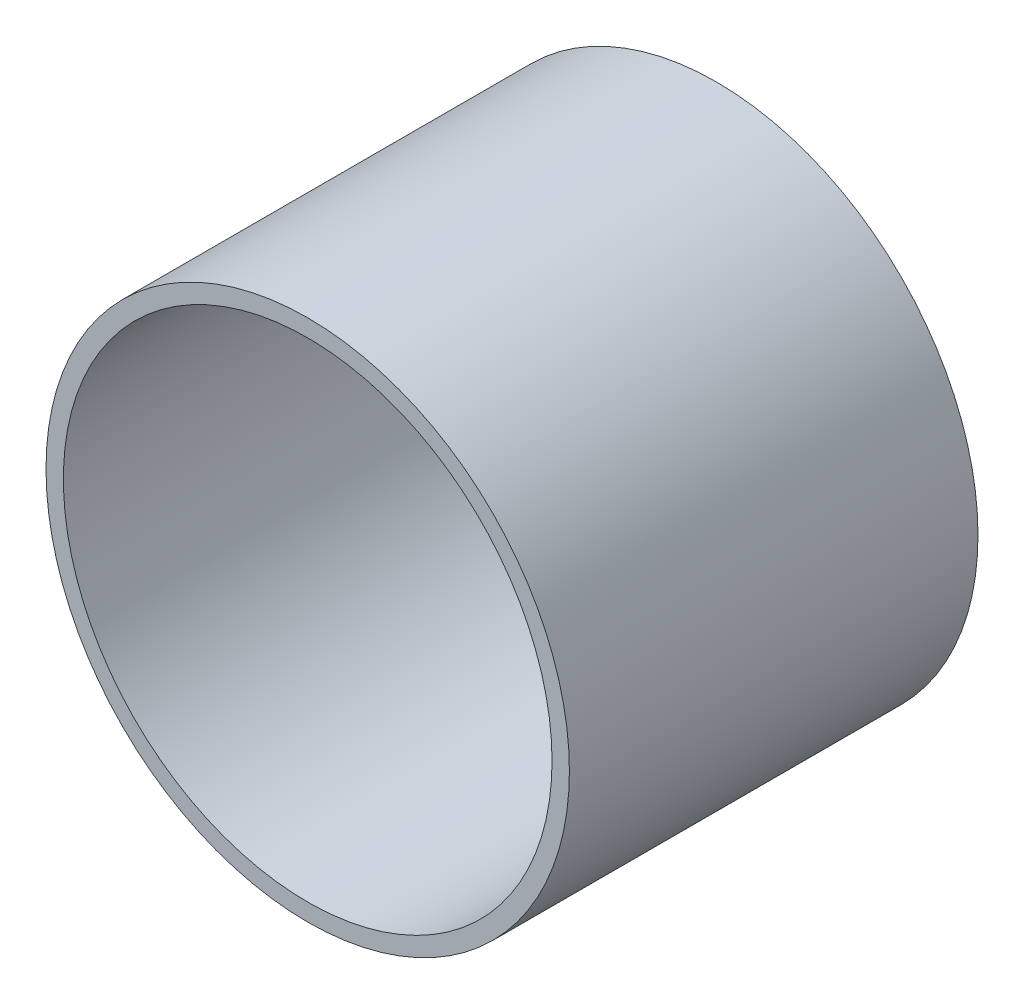
SolidWorks part; units mm, degrees
ref_plane "Front Plane" through (0, 0, 0) normal (0, 0, 1) x (1, 0, 0)
ref_plane "Top Plane" through (0, 0, 0) normal (0, 1, 0) x (1, 0, 0)
ref_plane "Right Plane" through (0, 0, 0) normal (1, 0, 0) x (0, 0, -1)
sketch "Sketch1" plane through (0, 0, 0) normal (0, 0, 1) x (1, 0, 0)
  circle A0 centre (0, 0) radius 30.3784
  circle A1 centre (0, 0) radius 32.5374
  dimension "D1" = 65.0748
  dimension "D2" = 2.159
extrude "Boss-Extrude1" add sketch "Sketch1" along normal blind 50.8
